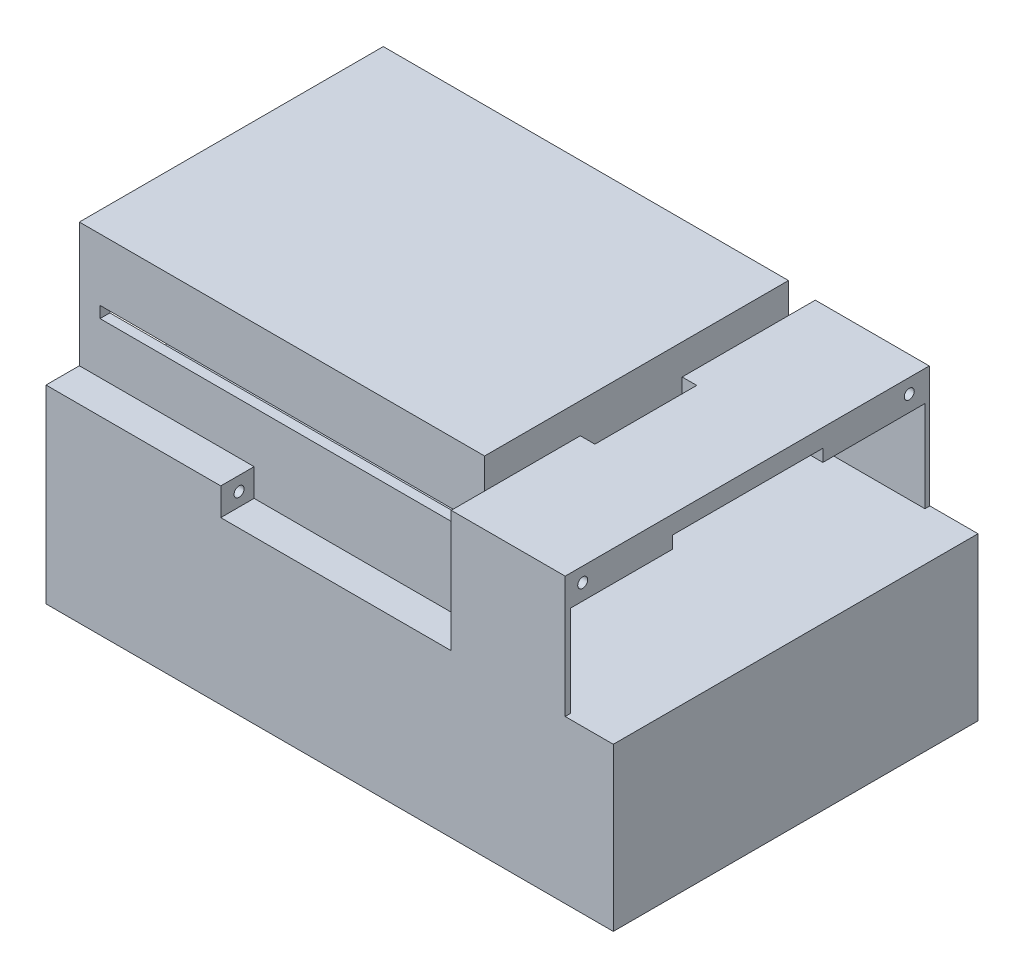
SolidWorks part; units mm, degrees
ref_plane "Front Plane" through (0, 0, 0) normal (0, 0, 1) x (1, 0, 0)
ref_plane "Top Plane" through (0, 0, 0) normal (0, 1, 0) x (1, 0, 0)
ref_plane "Right Plane" through (0, 0, 0) normal (1, 0, 0) x (0, 0, -1)
sketch "Sketch1" plane through (0, 0, 0) normal (0, 1, 0) x (1, 0, 0)
  line L1 (-71.12, 45.72) -> (71.12, 45.72)
  line L2 (-71.12, 45.72) -> (-71.12, -45.72)
  line L3 (-71.12, -45.72) -> (71.12, -45.72)
  line L4 (71.12, 45.72) -> (71.12, -45.72)
  line L5 (-71.12, 45.72) -> (71.12, -45.72) construction
  line L6 (-71.12, -45.72) -> (71.12, 45.72) construction
  line L11 (-68.58, 43.18) -> (68.58, -43.18) construction
  line L12 (-68.58, -43.18) -> (68.58, 43.18) construction
  point P0 (0, 0)
  point P6 (0, 0)
  dimension "D1" = 142.24
  dimension "D2" = 91.44
  dimension "D3" = 137.16
  dimension "D4" = 86.36
extrude "Boss-Extrude1" add sketch "Sketch1" along normal blind 40.64
sketch "Sketch2" plane through (71.12, 0, 0) normal (1, 0, 0) x (0, 0, -1)
  line L0 (-45.72, 40.64) -> (-45.72, 0) construction
  line L1 (-43.815, 38.735) -> (43.815, 38.735)
  line L2 (-43.815, 38.735) -> (-43.815, 1.905)
  line L3 (-43.815, 1.905) -> (43.815, 1.905)
  line L4 (43.815, 38.735) -> (43.815, 1.905)
  line L5 (-43.815, 38.735) -> (43.815, 1.905) construction
  line L6 (-43.815, 1.905) -> (43.815, 38.735) construction
  line L7 (45.72, 40.64) -> (45.72, 0) construction
  line L8 (-45.72, 40.64) -> (45.72, 40.64) construction
  line L9 (-45.72, 0) -> (45.72, 0) construction
  point P0 (0, 20.32)
  dimension "D1" = 1.905
  dimension "D2" = 1.905
  dimension "D3" = 1.905
  dimension "D4" = 1.905
sketch "Sketch3" plane through (0, 40.64, 0) normal (0, 1, 0) x (1, 0, 0)
  line L0 (-71.12, 45.72) -> (-71.12, -45.72) construction
  line L1 (-71.12, 38.844) -> (30.48, 38.844)
  line L2 (-71.12, 38.844) -> (-71.12, -37.356)
  line L3 (-71.12, -37.356) -> (30.48, -37.356)
  line L4 (30.48, 38.844) -> (30.48, -37.356)
  dimension "D1" = 101.6
  dimension "D2" = 76.2
  dimension "D3" = 0
extrude "Boss-Extrude2" add sketch "Sketch3" along normal blind 38.1
sketch "Sketch4" plane through (-71.12, 0, 0) normal (-1, 0, 0) x (0, 0, 1)
  line L1 (-35.9891, 75.9375) -> (34.8966, 75.9375)
  line L2 (-35.9891, 75.9375) -> (-35.9891, 41.298)
  line L3 (-35.9891, 41.298) -> (34.8966, 41.298)
  line L4 (34.8966, 75.9375) -> (34.8966, 41.298)
extrude "Cut-Extrude2" cut sketch "Sketch4" against normal blind 97.79 contours L2 L1 L4 L3
sketch "Sketch5" plane through (0, 0, 37.356) normal (0, 0, 1) x (1, 0, 0)
  line L1 (-65.9361, 63.2326) -> (24.9391, 63.2326)
  line L2 (-65.9361, 63.2326) -> (-65.9361, 60.3619)
  line L3 (-65.9361, 60.3619) -> (24.9391, 60.3619)
  line L4 (24.9391, 63.2326) -> (24.9391, 60.3619)
extrude "Cut-Extrude3" cut sketch "Sketch5" against normal blind 97.79
sketch "Sketch6" plane through (30.48, 0, 0) normal (1, 0, 0) x (0, 0, -1)
  line L1 (-31.4262, 71.0533) -> (32.5187, 71.0533)
  line L2 (-31.4262, 71.0533) -> (-31.4262, 47.9174)
  line L3 (-31.4262, 47.9174) -> (32.5187, 47.9174)
  line L4 (32.5187, 71.0533) -> (32.5187, 47.9174)
sketch "Sketch8" plane through (30.48, 0, 0) normal (1, 0, 0) x (0, 0, -1)
  line L1 (-45.72, 40.64) -> (45.5648, 40.64)
  line L2 (-45.72, 40.64) -> (-45.72, 71.12)
  line L3 (-45.72, 71.12) -> (45.5648, 71.12)
  line L4 (45.5648, 40.64) -> (45.5648, 71.12)
  dimension "D1" = 30.48
extrude "Boss-Extrude4" add sketch "Sketch8" along normal blind 28.575
sketch "Sketch9" plane through (59.055, 0, 0) normal (1, 0, 0) x (0, 0, -1)
  line L0 (-45.72, 40.64) -> (45.5648, 40.64) construction
  line L1 (-44.408, 63.5) -> (44.492, 63.5)
  line L2 (-44.408, 63.5) -> (-44.408, 40.64)
  line L3 (-44.408, 40.64) -> (44.492, 40.64)
  line L4 (44.492, 63.5) -> (44.492, 40.64)
  line L5 (-44.408, 63.5) -> (44.492, 40.64) construction
  line L6 (-44.408, 40.64) -> (44.492, 63.5) construction
  line L8 (-18.8103, 66.5843) -> (18.8943, 66.5843)
  line L9 (-18.8103, 66.5843) -> (-18.8103, 60.4157)
  line L10 (-18.8103, 60.4157) -> (18.8943, 60.4157)
  line L11 (18.8943, 66.5843) -> (18.8943, 60.4157)
  line L12 (-18.8103, 66.5843) -> (18.8943, 60.4157) construction
  line L13 (-18.8103, 60.4157) -> (18.8943, 66.5843) construction
  point P0 (0.042, 52.07)
  point P7 (0.042, 63.5)
  line M6 (-45.72, 40.64) -> (45.5648, 40.64)
  dimension "D1" = 22.86
  dimension "D2" = 0
  dimension "D3" = 88.9
extrude "Cut-Extrude4" cut sketch "Sketch9" against normal blind 28.321 contours L11 L8 L9 L1 | L11 L1 L9 L10 | L1 L11 L10 L9 L2 L4 M6
sketch "Sketch10" plane through (0, 71.12, 0) normal (0, 1, 0) x (1, 0, 0)
  line L0 (30.48, -31.4262) -> (30.48, 32.5187) construction
  line L1 (30.48, -13.3508) -> (34.1316, -13.3508)
  line L2 (30.48, -13.3508) -> (30.48, 12.1899)
  line L3 (30.48, 12.1899) -> (34.1316, 12.1899)
  line L4 (34.1316, -13.3508) -> (34.1316, 12.1899)
  dimension "D1" = 25.5407
extrude "Cut-Extrude5" cut sketch "Sketch10" against normal blind 14.097
extrude "Cut-Extrude6" cut sketch "Sketch2" against normal blind 225.933
sketch "Sketch12" plane through (71.12, 0, 0) normal (1, 0, 0) x (0, 0, -1)
  line L0 (-45.72, 40.64) -> (-45.72, 0) construction
  line L1 (-45.72, 40.64) -> (45.72, 40.64)
  line L2 (-45.72, 40.64) -> (-45.72, 0)
  line L3 (-45.72, 0) -> (45.72, 0)
  line L4 (45.72, 40.64) -> (45.72, 0)
  line L5 (-45.72, 40.64) -> (45.72, 40.64) construction
extrude "Boss-Extrude5" add sketch "Sketch12" against normal blind 2.667
sketch "Sketch13" plane through (-71.12, 0, 0) normal (-1, 0, 0) x (0, 0, 1)
  line L0 (-45.5648, 40.64) -> (-45.5648, 71.12) construction
  line L1 (-38.844, 40.64) -> (-45.5648, 40.64)
  line L2 (-38.844, 40.64) -> (-38.844, 47.5318)
  line L3 (-38.844, 47.5318) -> (-45.5648, 47.5318)
  line L4 (-45.5648, 40.64) -> (-45.5648, 47.5318)
  line L5 (45.72, 71.12) -> (45.72, 40.64) construction
  line L6 (37.356, 40.64) -> (45.72, 40.64)
  line L7 (37.356, 40.64) -> (37.356, 47.5318)
  line L8 (37.356, 47.5318) -> (45.72, 47.5318)
  line L9 (45.72, 40.64) -> (45.72, 47.5318)
  circle A0 centre (-41.8374, 43.9972) radius 1.25
  circle A1 centre (41.1304, 43.9972) radius 1.25
  dimension "D1" = 2.5
extrude "Boss-Extrude6" add sketch "Sketch13" against normal blind 43.815
sketch "Sketch14" plane through (59.055, 0, 0) normal (1, 0, 0) x (0, 0, -1)
  circle A0 centre (-41.3232, 67.5186) radius 1.25
  circle A1 centre (40.552, 67.5186) radius 1.25
extrude "Cut-Extrude7" cut sketch "Sketch14" against normal blind 13.843
sketch "Sketch15" plane through (71.12, 0, 0) normal (1, 0, 0) x (0, 0, -1)
  line L1 (-45.72, 40.64) -> (45.72, 40.64)
  line L2 (-45.72, 40.64) -> (-45.72, 0)
  line L3 (-45.72, 0) -> (45.72, 0)
  line L4 (45.72, 40.64) -> (45.72, 0)
